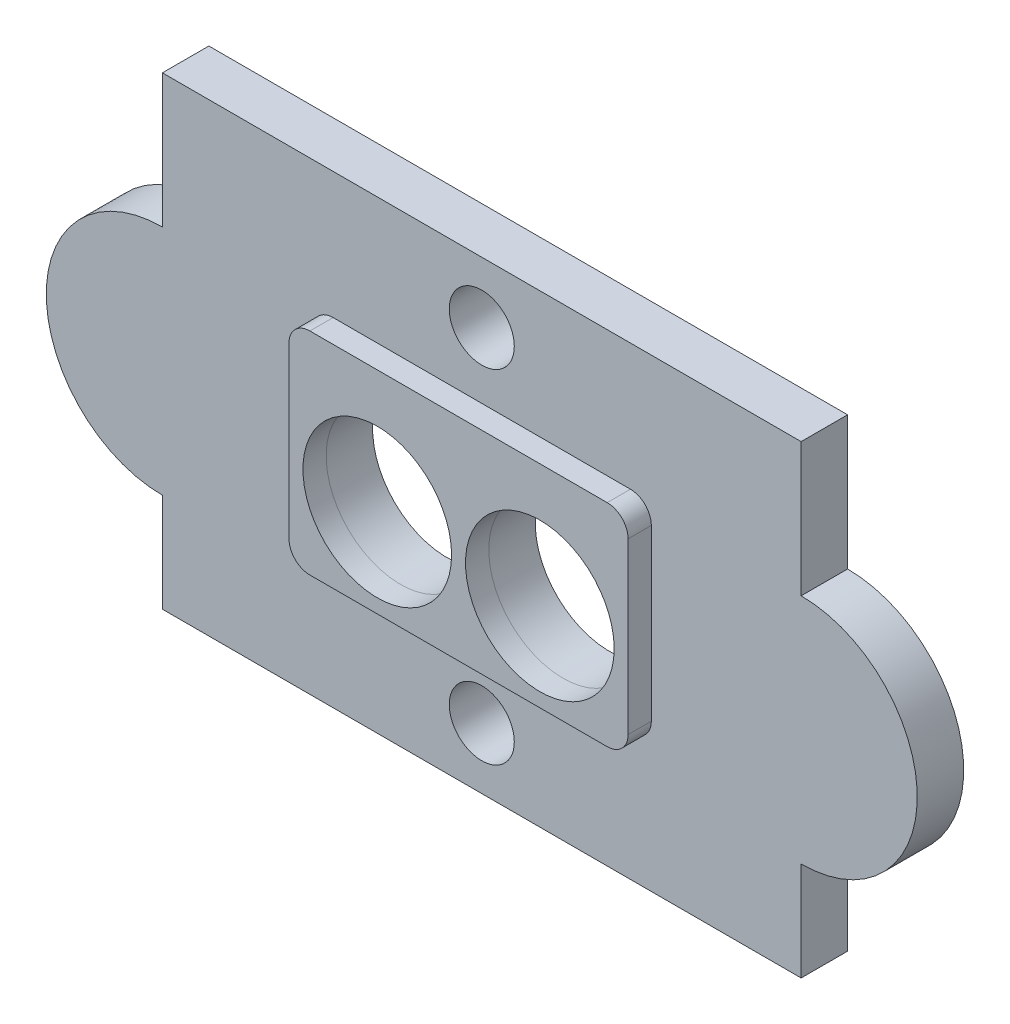
SolidWorks part; units mm, degrees
ref_plane "Front Plane" through (0, 0, 0) normal (0, 0, 1) x (1, 0, 0)
ref_plane "Top Plane" through (0, 0, 0) normal (0, 1, 0) x (1, 0, 0)
ref_plane "Right Plane" through (0, 0, 0) normal (1, 0, 0) x (0, 0, -1)
sketch "Sketch1" plane through (0, 0, 0) normal (0, 0, 1) x (1, 0, 0)
  line L0 (0, 4.75) -> (0, -4.75) construction
  line L1 (-7.5, -4.75) -> (7.5, -4.75)
  line L2 (-7.5, -4.75) -> (-7.5, 4.75)
  line L3 (-7.5, 4.75) -> (7.5, 4.75)
  line L4 (7.5, -4.75) -> (7.5, 4.75)
  line L5 (-7.5, -4.75) -> (7.5, 4.75) construction
  line L6 (-7.5, 4.75) -> (7.5, -4.75) construction
  line L7 (-3.5, -3.95) -> (-3.5, -4.75) construction
  line L8 (-13.75, -0.75) -> (13.75, -0.75)
  line L9 (-13.75, -10) -> (13.75, -10)
  line L10 (-13.75, -10) -> (-13.75, 10)
  line L11 (-13.75, 10) -> (13.75, 10)
  line L12 (13.75, -10) -> (13.75, 10)
  line L13 (-13.75, -10) -> (13.75, 10) construction
  line L14 (-13.75, 10) -> (13.75, -10) construction
  line L15 (-7.3, 4.55) -> (7.3, 4.55)
  line L16 (7.3, -4.55) -> (7.3, 4.55)
  line L17 (-7.3, -4.55) -> (7.3, -4.55)
  line L18 (-7.3, -4.55) -> (-7.3, 4.55)
  circle A0 centre (-3.5, -0.75) radius 3.2
  circle A1 centre (3.5, -0.75) radius 3.2
  point P0 (0, 0)
  point P13 (0, 0)
  dimension "D4" = 6.4
  dimension "D1" = 9.5
  dimension "D2" = 15
  dimension "D3" = 4
  dimension "D5" = 4
  dimension "D6" = 20
  dimension "D7" = 27.5
  dimension "D8" = 0.2
extrude "Boss-Extrude1" add sketch "Sketch1" along normal blind 1 contours L8 A1 L16 L15 L18 A0 | L8 A1 A0 L18 L17 L16
sketch "Sketch2" plane through (0, 0, 0) normal (0, 0, 1) x (1, 0, 0)
  line L0 (-13.75, -0.75) -> (13.75, -0.75) construction
  line L1 (-13.75, -0.75) -> (13.75, -0.75)
  line L2 (0, 10) -> (0, -10) construction
  line L4 (-7.5, -4.75) -> (7.5, -4.75)
  line L5 (7.5, -4.75) -> (7.5, 4.75)
  line L6 (7.5, 4.75) -> (-7.5, 4.75)
  line L7 (-7.5, 4.75) -> (-7.5, -4.75)
  line L8 (-7.5, -4.75) -> (7.5, -4.75)
  line L9 (7.5, -4.75) -> (7.5, 4.75)
  line L10 (7.5, 4.75) -> (-7.5, 4.75)
  line L11 (-7.5, 4.75) -> (-7.5, -4.75)
  line L12 (7.3, 4.55) -> (-7.3, 4.55)
  line L13 (7.3, -4.55) -> (7.3, 4.55)
  line L14 (-7.3, -4.55) -> (7.3, -4.55)
  line L15 (-7.3, 4.55) -> (-7.3, -4.55)
  line L16 (7.3, 4.55) -> (-7.3, 4.55)
  line L17 (7.3, -4.55) -> (7.3, 4.55)
  line L18 (-7.3, -4.55) -> (7.3, -4.55)
  line L19 (-7.3, 4.55) -> (-7.3, -4.55)
  line L20 (-13.75, -10) -> (13.75, -10)
  line L21 (-13.75, 10) -> (-13.75, -10)
  line L22 (13.75, 10) -> (-13.75, 10)
  line L23 (13.75, -10) -> (13.75, 10)
  line L24 (-13.75, -10) -> (13.75, -10)
  line L25 (-13.75, 10) -> (-13.75, -10)
  line L26 (13.75, 10) -> (-13.75, 10)
  line L27 (13.75, -10) -> (13.75, 10)
  arc A0 (-13.75, 4.25) -> (-13.75, -5.75) centre (-13.75, -0.75) ccw
  circle A1 centre (3.5, -0.75) radius 3.2
  circle A2 centre (3.5, -0.75) radius 3.2
  circle A3 centre (-3.5, -0.75) radius 3.2
  circle A4 centre (-3.5, -0.75) radius 3.2
  arc A5 (13.75, 4.25) -> (13.75, -5.75) centre (13.75, -0.75) cw
  dimension "D6" = 5
  dimension "D1" = 0
  dimension "D2" = 0
  dimension "D3" = 0
  dimension "D4" = 0
  dimension "D5" = 0
extrude "Boss-Extrude2" add sketch "Sketch2" against normal blind 2 separate body contours L25 A0 | A5 L27 | L2 L8 L11 L1 L25 L24 | L8 L2 L24 L27 L1 L9 | L2 L26 L25 L1 L11 L10 | L26 L2 L10 L9 L1 L27 | L2 L16 L19 L1 A4 | L16 L2 L1 A2 L17 | L1 L2 L18 L17 A2 | L2 L1 A4 L19 L18 | L2 L18 L19 L1 L11 L8 | L18 L2 L8 L9 L1 L17 | L2 L10 L11 L1 L19 L16 | L10 L2 L16 L17 L1 L9
sketch "Sketch3" plane through (0, 0, 0) normal (0, 0, 1) x (1, 0, 0)
  line L0 (-13.75, -0.75) -> (13.75, -0.75) construction
  line L1 (-13.75, -0.75) -> (13.75, -0.75)
  line L2 (0, 4.75) -> (0, 10) construction
  line L3 (13.75, 0) -> (-13.75, 0) construction
  line L4 (-7.5, -4.75) -> (7.5, -4.75)
  line L5 (7.5, -4.75) -> (7.5, 4.75)
  line L6 (7.5, 4.75) -> (-7.5, 4.75)
  line L7 (-7.5, 4.75) -> (-7.5, -4.75)
  line L8 (-7.5, -4.75) -> (7.5, -4.75)
  line L9 (7.5, -4.75) -> (7.5, 4.75)
  line L10 (7.5, 4.75) -> (-7.5, 4.75)
  line L11 (-7.5, 4.75) -> (-7.5, -4.75)
  line L12 (7.3, 4.55) -> (-7.3, 4.55)
  line L13 (7.3, -4.55) -> (7.3, 4.55)
  line L14 (-7.3, -4.55) -> (7.3, -4.55)
  line L15 (-7.3, 4.55) -> (-7.3, -4.55)
  line L16 (7.3, 4.55) -> (-7.3, 4.55)
  line L17 (7.3, -4.55) -> (7.3, 4.55)
  line L18 (-7.3, -4.55) -> (7.3, -4.55)
  line L19 (-7.3, 4.55) -> (-7.3, -4.55)
  line L20 (-13.75, -10) -> (13.75, -10)
  line L21 (-13.75, 10) -> (-13.75, -10)
  line L22 (13.75, 10) -> (-13.75, 10)
  line L23 (13.75, -10) -> (13.75, 10)
  line L24 (-13.75, -10) -> (13.75, -10)
  line L25 (-13.75, 10) -> (-13.75, -10)
  line L26 (13.75, 10) -> (-13.75, 10)
  line L27 (13.75, -10) -> (13.75, 10)
  circle A0 centre (0, 7.375) radius 1.4
  circle A1 centre (3.5, -0.75) radius 3.2
  circle A2 centre (3.5, -0.75) radius 3.2
  circle A3 centre (-3.5, -0.75) radius 3.2
  circle A4 centre (-3.5, -0.75) radius 3.2
  circle A5 centre (0, -7.375) radius 1.4
  dimension "D6" = 2.8
  dimension "D1" = 0
  dimension "D2" = 0
  dimension "D3" = 0
  dimension "D4" = 0
  dimension "D5" = 0
extrude "Cut-Extrude1" cut sketch "Sketch3" against normal through all contours L2 A0 | A0 L2 | A5
fillet "Fillet1" radius 0.9 4 edges at (-7.3, 4.55, 0.5) (7.3, 4.55, 0.5) (-7.3, -4.55, 0.5) (7.3, -4.55, 0.5)
sketch "Sketch4" [suppressed] plane through (0, 0, -2) normal (0, 0, -1) x (-1, 0, 0)
  line L0 (-10.6581, -7.2512) -> (-8.6581, -7.2512)
  line L1 (-11.6581, 3.7488) -> (-9.6581, 7.7488)
  line L2 (-8.6581, -7.2512) -> (-8.6581, 3.7488)
  line L3 (-8.6581, 3.7488) -> (-7.6581, 3.7488)
  line L4 (-7.6581, 3.7488) -> (-9.6581, 7.7488)
  line L5 (-9.6581, 7.7488) -> (-9.6581, -7.2512)
  line L6 (-10.6581, 3.7488) -> (-11.6581, 3.7488)
  line L7 (-10.6581, -7.2512) -> (-10.6581, 3.7488)
  dimension "D1" = 15
  dimension "D2" = 1
  dimension "D3" = 1
  dimension "D4" = 4
